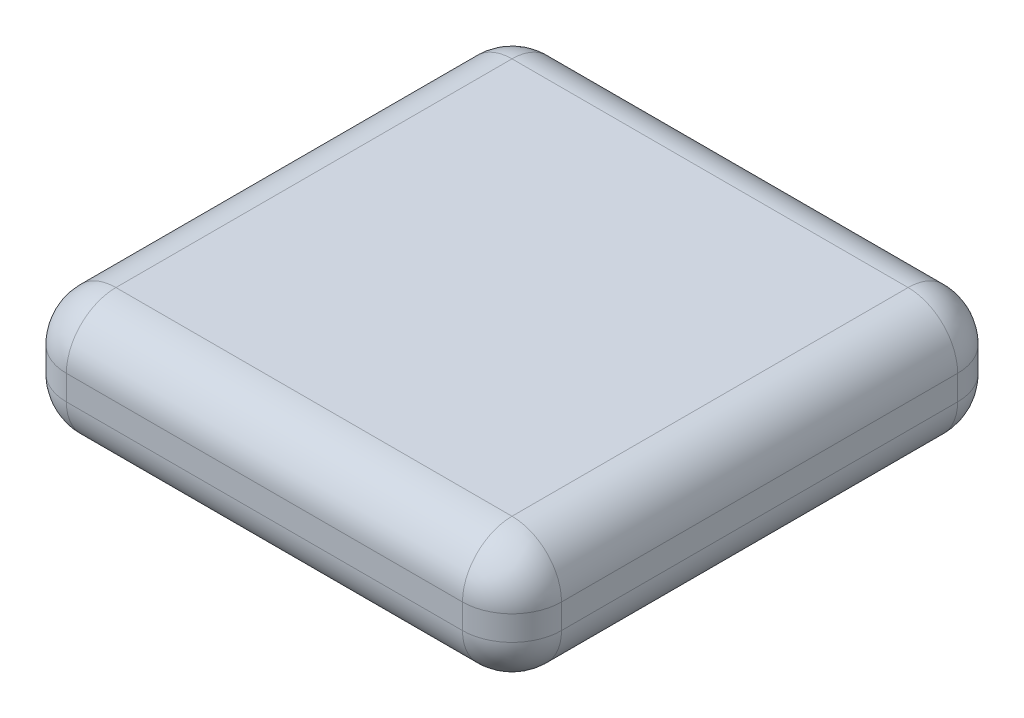
SolidWorks part; units mm, degrees
ref_plane "Ebene vorne" through (0, 0, 0) normal (0, 0, 1) x (1, 0, 0)
ref_plane "Ebene oben" through (0, 0, 0) normal (0, 1, 0) x (1, 0, 0)
ref_plane "Ebene rechts" through (0, 0, 0) normal (1, 0, 0) x (0, 0, -1)
sketch "Skizze1" plane through (0, 0, 0) normal (0, 1, 0) x (1, 0, 0)
  line L1 (-100, 100) -> (100, 100)
  line L2 (-100, 100) -> (-100, -100)
  line L3 (-100, -100) -> (100, -100)
  line L4 (100, 100) -> (100, -100)
  line L5 (-100, 100) -> (100, -100) construction
  line L6 (-100, -100) -> (100, 100) construction
  point P0 (0, 0)
  dimension "D1" = 200
  dimension "D2" = 200
extrude "Aufsatz-Linear austragen1" add sketch "Skizze1" along normal blind 50
fillet "Verrundung1" radius 20 12 edges at (100, 25, -100) (100, 25, 100) (-100, 25, 100) (-100, 0, 0) (-100, 25, -100) (0, 0, -100) (0, 50, -100) (100, 0, 0) (100, 50, 0) (0, 0, 100) (-100, 50, 0) (0, 50, 100)
